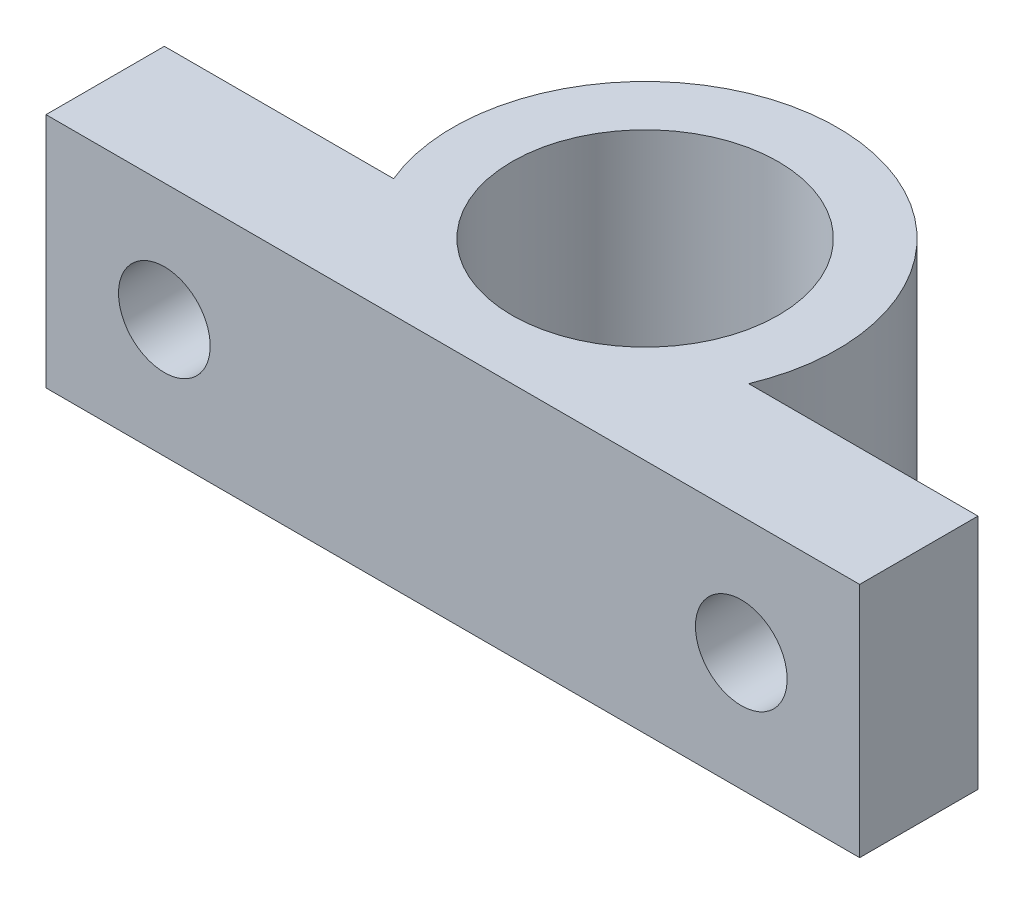
SolidWorks part; units mm, degrees
ref_plane "Front Plane" through (0, 0, 0) normal (0, 0, 1) x (1, 0, 0)
ref_plane "Top Plane" through (0, 0, 0) normal (0, 1, 0) x (1, 0, 0)
ref_plane "Right Plane" through (0, 0, 0) normal (1, 0, 0) x (0, 0, -1)
sketch "Sketch1" plane through (0, 0, 0) normal (0, 1, 0) x (1, 0, 0)
  circle A1 centre (0, 0) radius 6.5
  dimension "D1" = 13
extrude "Boss-Extrude1" add sketch "Sketch1" along normal blind 8
sketch "Sketch2" plane through (0, 8, 0) normal (0, 1, 0) x (1, 0, 0)
  line L0 (0, 0) -> (0, -6.5)
  circle A0 centre (0, 0) radius 6.5 construction
ref_plane "Plane1" through (0, 8, 6.5) normal (0, 0, 1) x (1, 0, 0)
sketch "Sketch3" plane through (0, 8, 6.5) normal (0, 0, 1) x (1, 0, 0)
  line L0 (-13.75, 0) -> (13.75, 0)
  line L1 (13.75, 0) -> (13.75, -8)
  line L2 (13.75, -8) -> (-13.75, -8)
  line L3 (-13.75, -8) -> (-13.75, 0)
  line L4 (-6.5, 0) -> (-6.5, -8) construction
  line L5 (6.5, 0) -> (-6.5, 0) construction
  dimension "D1" = 8
  dimension "D2" = 27.5
  dimension "D3" = 7.25
  dimension "D4" = 0
extrude "Boss-Extrude2" add sketch "Sketch3" against normal blind 4
sketch "Sketch4" plane through (0, 8, 0) normal (0, 1, 0) x (1, 0, 0)
  circle A0 centre (0, 0) radius 4.5
extrude "Cut-Extrude1" cut sketch "Sketch4" against normal up to next
sketch "Sketch5" plane through (0, 0, 2.5) normal (0, 0, -1) x (-1, 0, 0)
  line L0 (13.75, 8) -> (13.75, 0) construction
  line L1 (6, 8) -> (13.75, 8) construction
  line L2 (-13.75, 0) -> (-13.75, 8) construction
  line L3 (-6, 0) -> (-13.75, 0) construction
  circle A0 centre (9.75, 4) radius 1.55
  circle A1 centre (-9.75, 4) radius 1.55
  dimension "D1" = 3.1
  dimension "D4" = 4
  dimension "D2" = 4
  dimension "D3" = 4
  dimension "D5" = 4
extrude "Cut-Extrude2" cut sketch "Sketch5" against normal up to next
